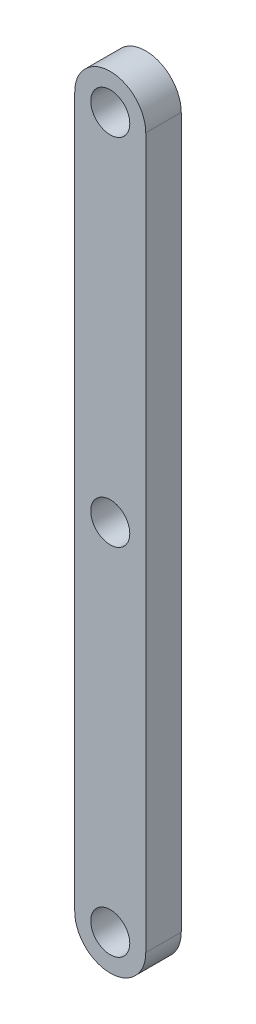
SolidWorks part; units mm, degrees
ref_plane "Alzado" through (0, 0, 0) normal (0, 0, 1) x (1, 0, 0)
ref_plane "Planta" through (0, 0, 0) normal (0, 1, 0) x (1, 0, 0)
ref_plane "Vista lateral" through (0, 0, 0) normal (1, 0, 0) x (0, 0, -1)
sketch "Croquis1" plane through (0, 0, 0) normal (0, 0, 1) x (1, 0, 0)
  line L2 (0, 0) -> (0, -40)
  line L4 (4, 0) -> (4, -40)
  arc A0 (4, 0) -> (0, 0) centre (2, 0) ccw
  arc A1 (0, -40) -> (4, -40) centre (2, -40) ccw
  circle A2 centre (2, 0) radius 1.1
  circle A3 centre (2, -40) radius 1.1
  circle A4 centre (2, -20) radius 1.1
  dimension "D3" = 2.2
  dimension "D4" = 2.2
  dimension "D6" = 2.2
  dimension "D1" = 40
  dimension "D2" = 4
  dimension "D5" = 20
extrude "Saliente-Extruir1" add sketch "Croquis1" along normal blind 2
